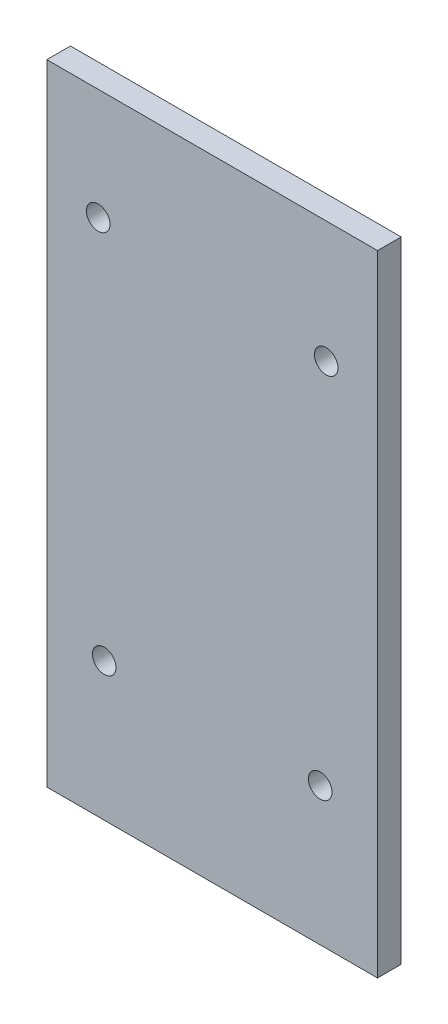
SolidWorks part; units mm, degrees
ref_plane "Front Plane" through (0, 0, 0) normal (0, 0, 1) x (1, 0, 0)
ref_plane "Top Plane" through (0, 0, 0) normal (0, 1, 0) x (1, 0, 0)
ref_plane "Right Plane" through (0, 0, 0) normal (1, 0, 0) x (0, 0, -1)
sketch "Schizzo1" plane through (0, 0, 0) normal (0, 0, 1) x (1, 0, 0)
  line L1 (35, 66.67) -> (-35, 66.67)
  line L2 (35, 66.67) -> (35, -66.67)
  line L3 (35, -66.67) -> (-35, -66.67)
  line L4 (-35, 66.67) -> (-35, -66.67)
  line L5 (35, 66.67) -> (-35, -66.67) construction
  line L6 (35, -66.67) -> (-35, 66.67) construction
  point P0 (0, 0)
  dimension "D1" = 70
  dimension "D2" = 133.34
extrude "Estrusione-Estrusione1" add sketch "Schizzo1" along normal blind 5
sketch "Schizzo2" plane through (0, 0, 5) normal (0, 0, 1) x (1, 0, 0)
  line L0 (-22.86, 0) -> (-22.86, -66.67) construction
  line L1 (22.86, 0) -> (22.86, -66.67) construction
  line L2 (-35, 0) -> (35, 0) construction
  line L3 (-24.13, 66.67) -> (-24.13, 0) construction
  line L4 (-35, 66.67) -> (-35, -66.67)
  line L5 (-35, -66.67) -> (35, -66.67)
  line L6 (35, -66.67) -> (35, 66.67)
  line L7 (35, 66.67) -> (-35, 66.67)
  line L8 (-35, 66.67) -> (-35, -66.67)
  line L9 (-35, -66.67) -> (35, -66.67)
  line L10 (35, -66.67) -> (35, 66.67)
  line L11 (35, 66.67) -> (-35, 66.67)
  line L12 (24.13, 66.67) -> (24.13, 0) construction
  line L13 (-24.13, 51.373) -> (24.13, 51.373) construction
  line L14 (0, 56.67) -> (0, 0) construction
  line L15 (-22.86, -37.46) -> (22.86, -37.46) construction
  circle A0 centre (-24.13, 43.15) radius 2.5
  circle A1 centre (24.13, 40.95) radius 2.5
  circle A2 centre (-22.86, -37.46) radius 2.5
  circle A3 centre (22.86, -37.46) radius 2.5
  point P21 (0, 0)
  point P23 (0, 51.373)
  point P29 (0, -37.46)
  dimension "D4" = 5
  dimension "D2" = 45.72
  dimension "D3" = 48.26
  dimension "D5" = 25.72
  dimension "D6" = 23.52
  dimension "D7" = 29.21
  dimension "D1" = 0
extrude "Taglio-Estrusione1" cut sketch "Schizzo2" against normal blind 20 contours A0 | A1 | A3 | A2
